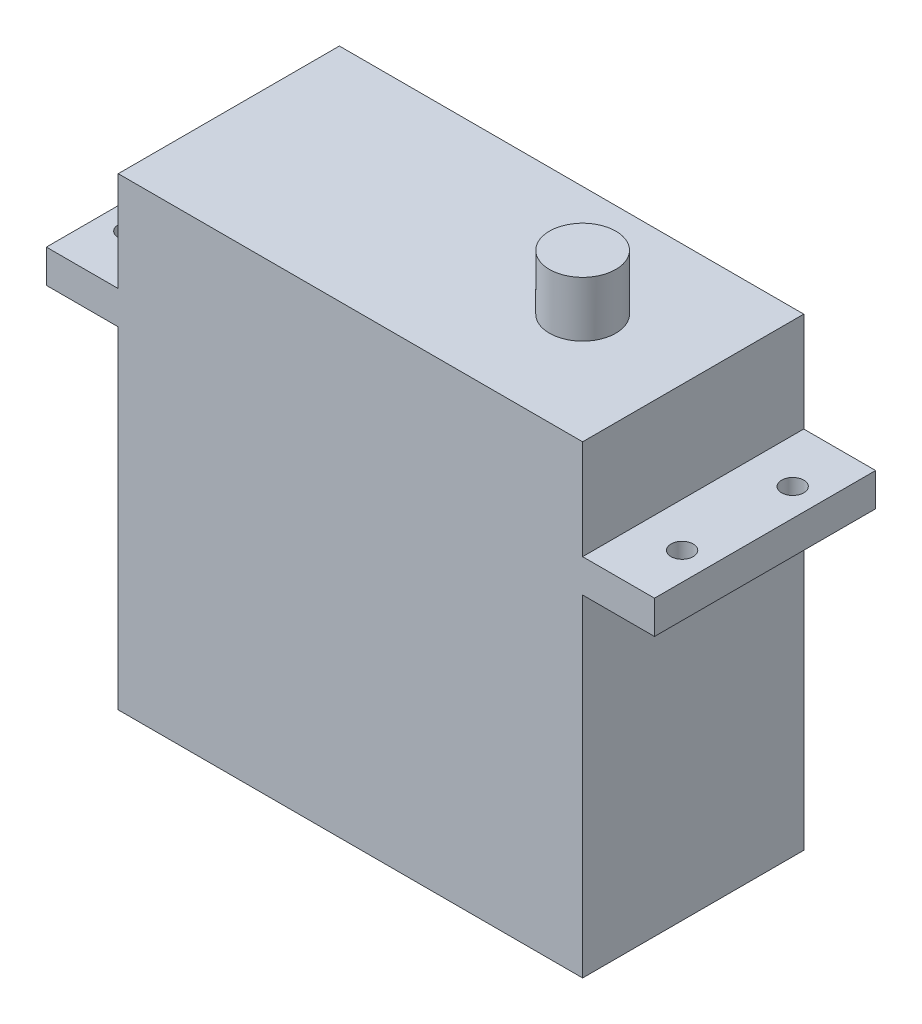
SolidWorks part; units mm, degrees
ref_plane "Front Plane" through (0, 0, 0) normal (0, 0, 1) x (1, 0, 0)
ref_plane "Top Plane" through (0, 0, 0) normal (0, 1, 0) x (1, 0, 0)
ref_plane "Right Plane" through (0, 0, 0) normal (1, 0, 0) x (0, 0, -1)
sketch "Sketch1" plane through (0, 0, 0) normal (0, 1, 0) x (1, 0, 0)
  line L1 (0, 0) -> (42, 0)
  line L2 (0, 0) -> (0, 20)
  line L3 (0, 20) -> (42, 20)
  line L4 (42, 0) -> (42, 20)
  dimension "D1" = 20
  dimension "D2" = 42
extrude "Boss-Extrude1" add sketch "Sketch1" along normal blind 42
sketch "Sketch2" plane through (0, 0, 0) normal (0, 0, 1) x (1, 0, 0)
  line L1 (-6.5, 30) -> (48.5, 30)
  line L2 (-6.5, 30) -> (-6.5, 33)
  line L3 (-6.5, 33) -> (48.5, 33)
  line L4 (48.5, 30) -> (48.5, 33)
  line L5 (0, 42) -> (0, 0) construction
  dimension "D1" = 30
  dimension "D2" = 3
  dimension "D3" = 55
  dimension "D4" = 6.5
extrude "Boss-Extrude2" add sketch "Sketch2" against normal up to surface (20 mm away) up to face at (21, 21, -20)
sketch "Sketch3" plane through (0, 33, 0) normal (0, 1, 0) x (1, 0, 0)
  line L0 (0, 0) -> (-6.5, 0) construction
  line L2 (-6.5, 20) -> (-6.5, 0) construction
  line L3 (48.5, 20) -> (48.5, 0) construction
  circle A0 centre (-4, 15) radius 1
  circle A1 centre (-4, 5) radius 1
  circle A2 centre (46, 15) radius 1
  circle A3 centre (46, 5) radius 1
  point P8 (-3.25, 0)
  dimension "D1" = 2
  dimension "D2" = 2
  dimension "D3" = 2
  dimension "D4" = 2
  dimension "D5" = 10
  dimension "D6" = 10
  dimension "D7" = 50
  dimension "D8" = 5
  dimension "D9" = 2.5
  dimension "D10" = 2.5
  dimension "D11" = 2.5
  dimension "D12" = 2.5
extrude "Cut-Extrude1" cut sketch "Sketch3" against normal blind 42
sketch "Sketch4" plane through (0, 42, 0) normal (0, 1, 0) x (1, 0, 0)
  line L0 (42, 0) -> (42, 20) construction
  line L1 (0, 0) -> (42, 0) construction
  circle A0 centre (32, 10) radius 3
  point P2 (42, 10)
  dimension "D1" = 6
  dimension "D2" = 10
  dimension "D3" = 10
extrude "Boss-Extrude3" add sketch "Sketch4" along normal blind 5
